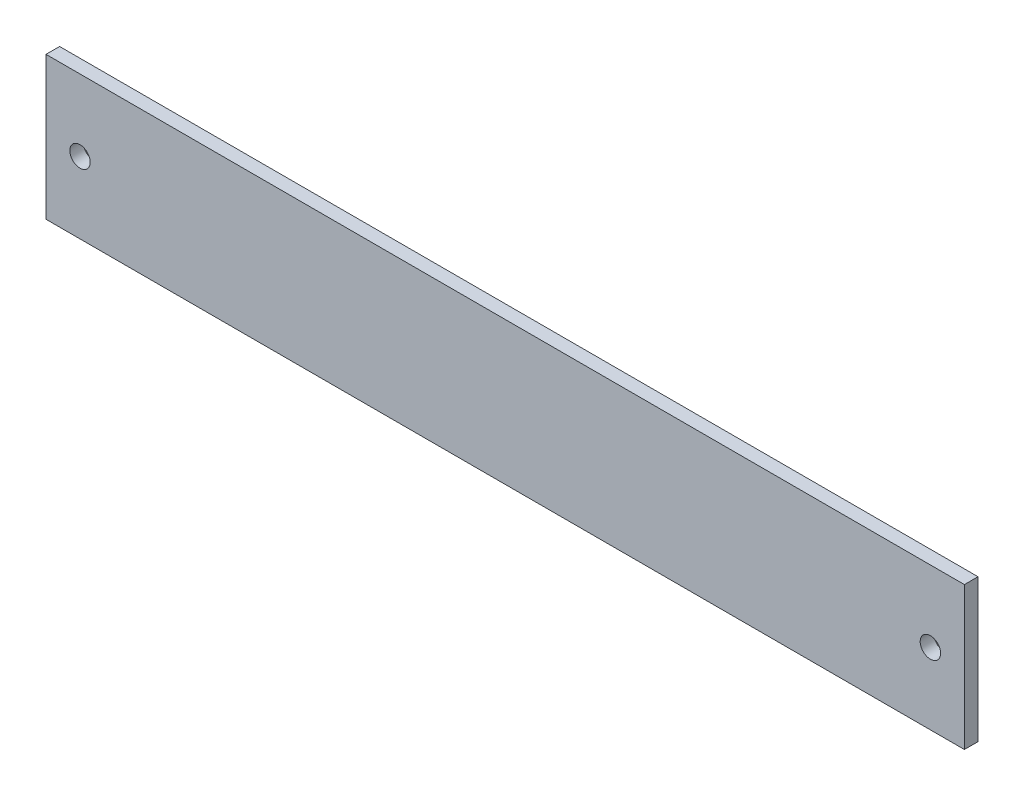
SolidWorks part; units mm, degrees
ref_plane "Front Plane" through (0, 0, 0) normal (0, 0, 1) x (1, 0, 0)
ref_plane "Top Plane" through (0, 0, 0) normal (0, 1, 0) x (1, 0, 0)
ref_plane "Right Plane" through (0, 0, 0) normal (1, 0, 0) x (0, 0, -1)
sketch "Sketch1" plane through (0, 0, 0) normal (0, 0, 1) x (1, 0, 0)
  line L1 (67.5, -10.5) -> (-67.5, -10.5)
  line L2 (67.5, -10.5) -> (67.5, 10.5)
  line L3 (67.5, 10.5) -> (-67.5, 10.5)
  line L4 (-67.5, -10.5) -> (-67.5, 10.5)
  line L5 (67.5, -10.5) -> (-67.5, 10.5) construction
  line L6 (67.5, 10.5) -> (-67.5, -10.5) construction
  circle A0 centre (-62.5, 0) radius 1.5
  circle A1 centre (62.5, 0) radius 1.5
  point P0 (0, 0)
  dimension "D3" = 3
  dimension "D4" = 5
  dimension "D5" = 5
  dimension "D6" = 3
  dimension "D7" = 10.5
  dimension "D1" = 21
  dimension "D2" = 135
extrude "Boss-Extrude1" add sketch "Sketch1" along normal blind 2
